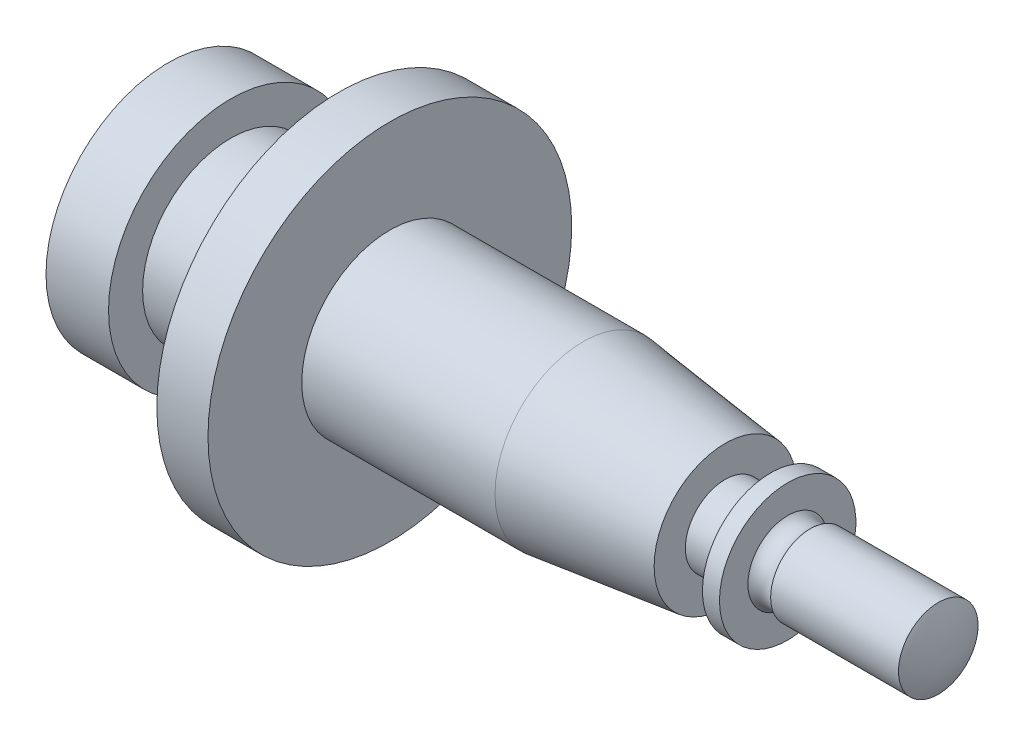
SolidWorks part; units mm, degrees
ref_plane "Ön Düzlem" through (0, 0, 0) normal (0, 0, 1) x (1, 0, 0)
ref_plane "Üst Düzlem" through (0, 0, 0) normal (0, 1, 0) x (1, 0, 0)
ref_plane "Sağ Düzlem" through (0, 0, 0) normal (1, 0, 0) x (0, 0, -1)
sketch "Çizim1" plane through (0, 0, 0) normal (0, 0, 1) x (1, 0, 0)
  line L0 (0, 0) -> (137, 0) construction
  line L1 (0, 0) -> (0, 21.5)
  line L2 (0, 21.5) -> (11, 21.5)
  line L3 (11, 21.5) -> (11, 15.5)
  line L4 (11, 15.5) -> (30, 15.5)
  line L5 (30, 15.5) -> (30, 32)
  line L6 (30, 32) -> (39, 32)
  line L7 (39, 32) -> (39, 15.5)
  line L8 (39, 15.5) -> (73, 15.5)
  line L9 (73, 15.5) -> (98, 12.5)
  line L10 (98, 12.5) -> (98, 7)
  line L11 (98, 7) -> (106, 7)
  line L12 (106, 7) -> (106, 12)
  line L13 (106, 12) -> (109, 12)
  line L14 (109, 12) -> (109, 7)
  line L15 (113, 7) -> (135.5, 7)
  line L16 (0, 0) -> (137, 0)
  arc A0 (109, 7) -> (113, 7) centre (111, 9.2361) ccw
  arc A1 (137, 0) -> (135.5, 7) centre (122.0067, 0.4479) ccw
  dimension "D14" = 3
  dimension "D18" = 15
  dimension "D1" = 21.5
  dimension "D2" = 11
  dimension "D3" = 15.5
  dimension "D4" = 19
  dimension "D5" = 32
  dimension "D6" = 9
  dimension "D7" = 73
  dimension "D8" = 12.5
  dimension "D9" = 25
  dimension "D10" = 7
  dimension "D11" = 8
  dimension "D12" = 12
  dimension "D13" = 3
  dimension "D15" = 28
  dimension "D17" = 1.5
revolve "Döndür2" add sketch "Çizim1" angle 360 about L0
